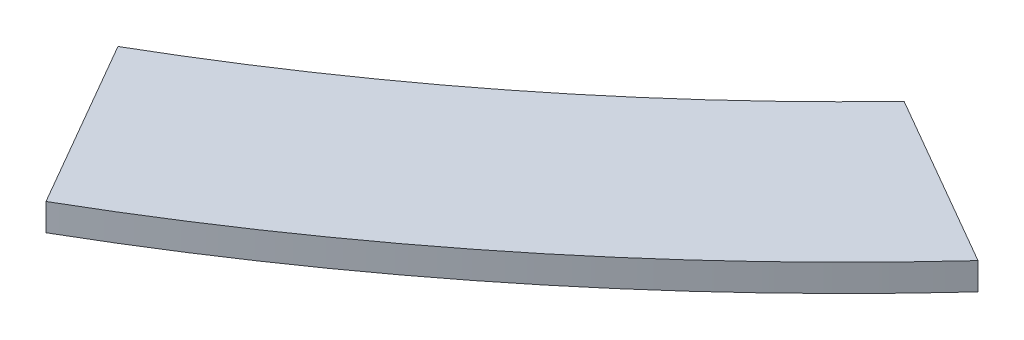
SolidWorks part; units mm, degrees
material "PTFE (general)"
ref_plane "Front Plane" through (0, 0, 0) normal (0, 0, 1) x (1, 0, 0)
ref_plane "Top Plane" through (0, 0, 0) normal (0, 1, 0) x (1, 0, 0)
ref_plane "Right Plane" through (0, 0, 0) normal (1, 0, 0) x (0, 0, -1)
sketch "Sketch1" plane through (0, 0, 0) normal (0, 1, 0) x (1, 0, 0)
  line L0 (-13.335, -54.2656) -> (-13.335, -59.9391)
  line L1 (13.335, -54.2656) -> (13.335, -59.9391)
  line L2 (0, 0) -> (53.1779, -30.7022)
  line L3 (40.3279, -38.6812) -> (45.2412, -41.518)
  line L4 (0, 0) -> (41.2834, -71.505)
  line L5 (0, 0) -> (-69.401, -7.9072) construction
  line L6 (0, 0) -> (0, -23.1086) construction
  line L7 (13.335, -59.9391) -> (45.2412, -41.518) construction
  circle A0 centre (0, 0) radius 55.88
  circle A1 centre (0, 0) radius 76.2
  circle A2 centre (0, 0) radius 59.69
  circle A5 centre (0, 0) radius 61.4045
  dimension "D1" = 111.76
  dimension "D2" = 152.4
  dimension "D4" = 13.335
  dimension "D5" = 13.335
  dimension "D9" = 69.85
  dimension "D10" = 83.5
  dimension "D7" = 5.5245
  dimension "D6" = 60
  dimension "D8" = 13.335
  dimension "D11" = 36.8422
  dimension "D12" = 18.4211
  dimension "D3" = 3.81
extrude "Boss-Extrude1" add sketch "Sketch1" along normal blind 0.762 contours L4 A2 L3 A0 | L4 A5 L3 A2
equation "\"Middle Coupler Inner Daimeter\"= 3.875in"
equation "\"Middle Coupler  Wall Thickness\" = 0.25in"
equation "\"Middle Coupler Bottom Thickness\"= 0.2in"
equation "\"Bearing Rail Offset\"= 0.45in"
equation "\"3-56 UNF Tap\"= 0.089in"
equation "\"3-56 UNF Clearance\"= 0.104in"
equation "\"Ball Bearing Distance\"= 0.03in"
equation "\"D1@Sketch1\"=\"Middle Coupler Inner Daimeter\"+0.5+0.0125*2in"
equation "\"TCA Outer Diameter\" = 6in"
equation "\"D2@Sketch1\"=\"TCA Outer Diameter\""
equation "\"D4@Sketch1\"=0.50 + (0.05/2)"
equation "\"D5@Sketch1\"=\"D4@Sketch1\""
equation "\"Interstage Aeroframe Wall Thickness\" = 0.072in"
equation "\"Compression Spring OD\"= 0.42in"
equation "\"10-24 Tap\"= 0.157in"
equation "\"10-24 Clearance\"= 0.196in"
equation "\"D3@Sketch1\"=0.125in+(0.05/2)"
equation "\"Lower Stage Fuselage Wall Thickness\" = 0.25in"
equation "\"6-32 Tap\" = 0.107in"
equation "\"1/4-20 Tap\" = 0.201in"
equation "\"3-48 Tap\"= 0.079in"
equation "\"12-24 Tap\" = 0.177in"
equation "\"3-48 Clearance\" = 0.104in"
equation "\"6-32 Clearance\" = 0.144"
equation "\"D9@Sketch1\"=(\"D2@Sketch1\"-0.5)/2"
equation "\"D1@Boss-Extrude1\"=3/16"
equation "\"D7@Sketch1\"=3/16 + 0.03"
equation "\"D8@Sketch1\"=\"D4@Sketch1\""
equation "\"D12@Sketch1\"=\"D11@Sketch1\"/2"
